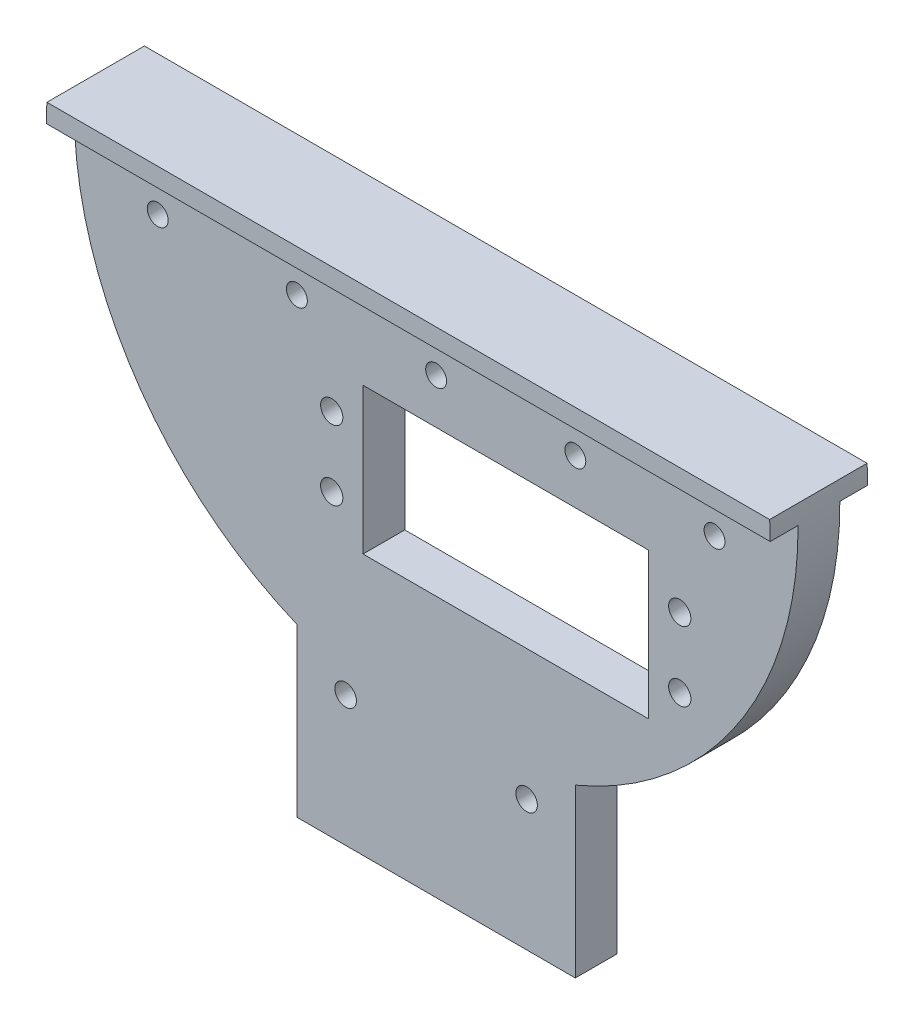
SolidWorks part; units mm, degrees
ref_plane "前视基准面" through (0, 0, 0) normal (0, 0, 1) x (1, 0, 0)
ref_plane "上视基准面" through (0, 0, 0) normal (0, 1, 0) x (1, 0, 0)
ref_plane "右视基准面" through (0, 0, 0) normal (1, 0, 0) x (0, 0, -1)
sketch "草图1" plane through (0, 0, 0) normal (0, 0, 1) x (1, 0, 0)
  line L0 (-48.4516, 46.7365) -> (55.5484, 46.7365)
  line L1 (55.5484, 46.7365) -> (55.5484, 43.7365)
  line L2 (-48.4516, 46.7365) -> (-48.4264, 43.7365)
  line L3 (-6.9516, 30.2365) -> (34.0484, 30.2365)
  line L4 (34.0484, 30.2365) -> (34.0484, 9.2365)
  line L5 (34.0484, 9.2365) -> (-6.9516, 9.2365)
  line L6 (-6.9516, 9.2365) -> (-6.9516, 30.2365)
  line L8 (-16.4516, -8.2635) -> (-16.4516, -4.2635)
  line L9 (23.5484, -4.2635) -> (23.5484, -8.2635)
  line L10 (-16.4516, -4.2635) -> (-16.4516, -24.2635)
  line L11 (-16.4516, -24.2635) -> (23.5484, -24.2635)
  line L12 (23.5484, -24.2635) -> (23.5484, -4.2635)
  arc A0 (55.5484, 43.7365) -> (23.5484, -4.2635) centre (3.5484, 43.7365) cw
  circle A1 centre (-11.4516, 24.7365) radius 1.6
  circle A2 centre (-11.4516, 14.7365) radius 1.6
  circle A3 centre (38.5484, 24.7365) radius 1.6
  circle A4 centre (38.5484, 14.7365) radius 1.6
  circle A5 centre (-36.4516, 36.7365) radius 1.5
  circle A6 centre (-16.4516, 36.7365) radius 1.5
  circle A7 centre (3.5484, 36.7365) radius 1.5
  circle A8 centre (23.5484, 36.7365) radius 1.5
  circle A9 centre (43.5484, 36.7365) radius 1.5
  arc A10 (-16.4516, -4.2635) -> (-48.4516, 43.7365) centre (3.5484, 43.7365) cw
  arc A11 (-48.365, 46.7365) -> (-16.4516, -4.2635) centre (3.5484, 43.7365) ccw
  arc A12 (23.5484, -4.2635) -> (55.4618, 46.7365) centre (3.5484, 43.7365) ccw
extrude "凸台-拉伸1" add sketch "草图1" along normal blind 14
sketch "草图2" plane through (23.5484, 0, 0) normal (1, 0, 0) x (0, 0, -1)
  line L0 (-14, 46.7365) -> (-14, 44.0365)
  line L1 (-14, 46.7365) -> (-14, -4.2635) construction
  line L2 (-14, 44.0365) -> (-10, 44.0365)
  line L3 (-10, 44.0365) -> (-10, -24.2635)
  line L4 (-14, -24.2635) -> (0, -24.2635) construction
  line L5 (-10, -24.2635) -> (-4, -24.2635)
  line L6 (-4, -24.2635) -> (-4, 44.0365)
  line L7 (-4, 44.0365) -> (0, 44.0365)
  line L8 (0, -4.2635) -> (0, 46.7365) construction
  line L9 (0, 44.0365) -> (0, 46.7365)
  line L10 (0, 46.7365) -> (-14, 46.7365)
  line L11 (-14, 44.0365) -> (-14, -24.2635)
  line L12 (-14, -24.2635) -> (-10, -24.2635)
  line L13 (-10, 44.0365) -> (-14, 44.0365)
  line L14 (0, 44.0365) -> (0, -24.2635)
  line L15 (0, -24.2635) -> (-4, -24.2635)
  line M3 (0, -24.2635) -> (0, -4.2635)
  line M4 (0, -4.2635) -> (-14, -4.2635)
  line M5 (-14, -4.2635) -> (-14, -24.2635)
  line M6 (-14, -24.2635) -> (0, -24.2635)
extrude "切除-拉伸1" cut sketch "草图2" against normal through all both and the other way through all contours L3 M4 M5 M6 | L2 L11 L3 M4 | L14 L7 L6 M4 | L6 M6 M3 M4
sketch "草图3" plane through (0, 0, 4) normal (0, 0, -1) x (-1, 0, 0)
  line L0 (-23.5484, -24.2635) -> (-23.5484, -28.2635)
  line L1 (-23.5484, -28.2635) -> (16.4516, -28.2635)
  line L2 (16.4516, -28.2635) -> (16.4516, -24.2635)
  line L3 (16.4516, -24.2635) -> (-23.5484, -24.2635)
extrude "凸台-拉伸2" add sketch "草图3" against normal blind 6
sketch "草图4" plane through (0, 0, 4) normal (0, 0, -1) x (-1, 0, 0)
  circle A0 centre (-16.5484, -9.5135) radius 1.55
  circle A1 centre (9.4516, -9.5135) radius 1.55
extrude "切除-拉伸2" cut sketch "草图4" against normal through all both and the other way through all
